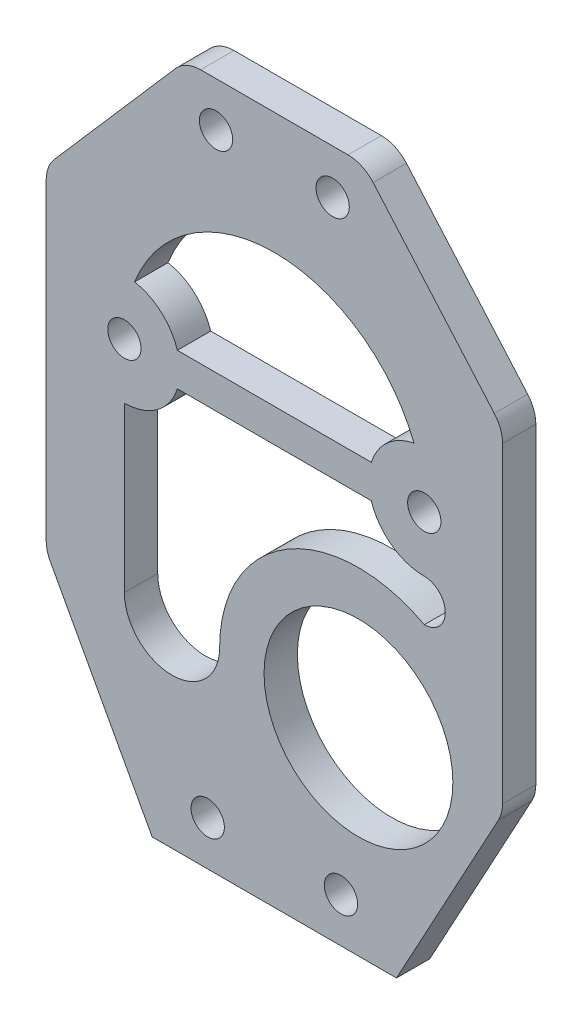
SolidWorks part; units mm, degrees
ref_plane "Ön Düzlem" through (0, 0, 0) normal (0, 0, 1) x (1, 0, 0)
ref_plane "Üst Düzlem" through (0, 0, 0) normal (0, 1, 0) x (1, 0, 0)
ref_plane "Sağ Düzlem" through (0, 0, 0) normal (1, 0, 0) x (0, 0, -1)
sketch "Çizim3" plane through (0, 0, 0) normal (0, 0, 1) x (1, 0, 0)
  line L0 (0, 0) -> (0, 21.4413) construction
  line L1 (-11, 0) -> (11, 0)
  line L2 (11, 0) -> (20.5432, 17.5763)
  line L3 (20.5432, 17.5763) -> (20.5432, 47.5763)
  line L4 (20.5432, 47.5763) -> (8, 62)
  line L5 (8, 62) -> (-8, 62)
  line L6 (-11, 0) -> (-20.5432, 17.5763)
  line L7 (-20.5432, 17.5763) -> (-20.5432, 47.5763)
  line L8 (-20.5432, 47.5763) -> (-8, 62)
  line L9 (-6, 4) -> (6, 4) construction
  line L10 (0, 21.4413) -> (0, 36.0763) construction
  line L11 (-5.25, 57.99) -> (5.25, 57.99) construction
  line L12 (-8.7303, 36.0763) -> (8.7303, 36.0763)
  line L15 (10.9176, 22.8026) -> (12.2913, 24.8615) construction
  line L16 (20.5432, 17.5763) -> (6.5893, 25.1527) construction
  line L17 (-13.5, 32.5763) -> (-13.5, 17.7908)
  line L18 (0, 17.7908) -> (-0.9262, 17.7908) construction
  line L20 (13.5, 32.5763) -> (13.5, 28.7967) construction
  line L22 (0, 39.0763) -> (0, 92.7459) construction
  line L23 (-8.7303, 39.0763) -> (8.7303, 39.0763)
  circle A0 centre (-6, 4) radius 1.5
  circle A1 centre (6, 4) radius 1.5
  circle A2 centre (-5.25, 57.99) radius 1.5
  circle A3 centre (5.25, 57.99) radius 1.5
  circle A4 centre (-13.5, 37.5763) radius 1.5
  circle A5 centre (13.5, 37.5763) radius 1.5
  arc A6 (12.5741, 42.4899) -> (8.7303, 39.0763) centre (13.5, 37.5763) ccw
  arc A7 (-8.7303, 39.0763) -> (-12.5741, 42.4899) centre (-13.5, 37.5763) ccw
  circle A9 centre (7.5738, 17.7908) radius 8.5
  arc A10 (13.5, 28.7967) -> (-4.9262, 17.7908) centre (7.5738, 17.7908) ccw
  arc A11 (-13.5, 17.7908) -> (-4.9262, 17.7908) centre (-9.2131, 17.7908) ccw
  arc A12 (13.5, 28.7967) -> (13.5, 32.5763) centre (13.5, 30.6865) ccw
  arc A13 (20.0178, 16.6087) -> (20.0738, 17.8312) centre (7.5738, 17.7908) ccw
  arc A15 (8.7303, 36.0763) -> (13.5, 32.5763) centre (13.5, 37.5763) ccw
  arc A16 (-13.5, 32.5763) -> (-8.7303, 36.0763) centre (-13.5, 37.5763) ccw
  arc A17 (12.5741, 42.4899) -> (-12.5741, 42.4899) centre (0, 37.5763) ccw
  point P12 (0, 62)
  dimension "D9" = 3
  dimension "D10" = 3
  dimension "D14" = 3
  dimension "D15" = 3
  dimension "D20" = 3
  dimension "D21" = 3
  dimension "D22" = 10
  dimension "D23" = 10
  dimension "D25" = 17
  dimension "D26" = 25
  dimension "D1" = 11
  dimension "D2" = 20
  dimension "D3" = 30
  dimension "D4" = 8
  dimension "D5" = 62
  dimension "D6" = 118.5
  dimension "D7" = 12
  dimension "D8" = 6
  dimension "D11" = 4
  dimension "D12" = 10.5
  dimension "D13" = 5.25
  dimension "D16" = 4.01
  dimension "D17" = 10
  dimension "D18" = 27
  dimension "D19" = 13.5
  dimension "D27" = 11.5
  dimension "D28" = 6
extrude "Yükseklik-Ekstrüzyon1" add sketch "Çizim3" along normal blind 3
fillet "Radyus1" radius 3 6 edges at (20.5432, 17.5763, 1.5) (20.5432, 47.5763, 1.5) (8, 62, 1.5) (-8, 62, 1.5) (-20.5432, 47.5763, 1.5) (-20.5432, 17.5763, 1.5)
